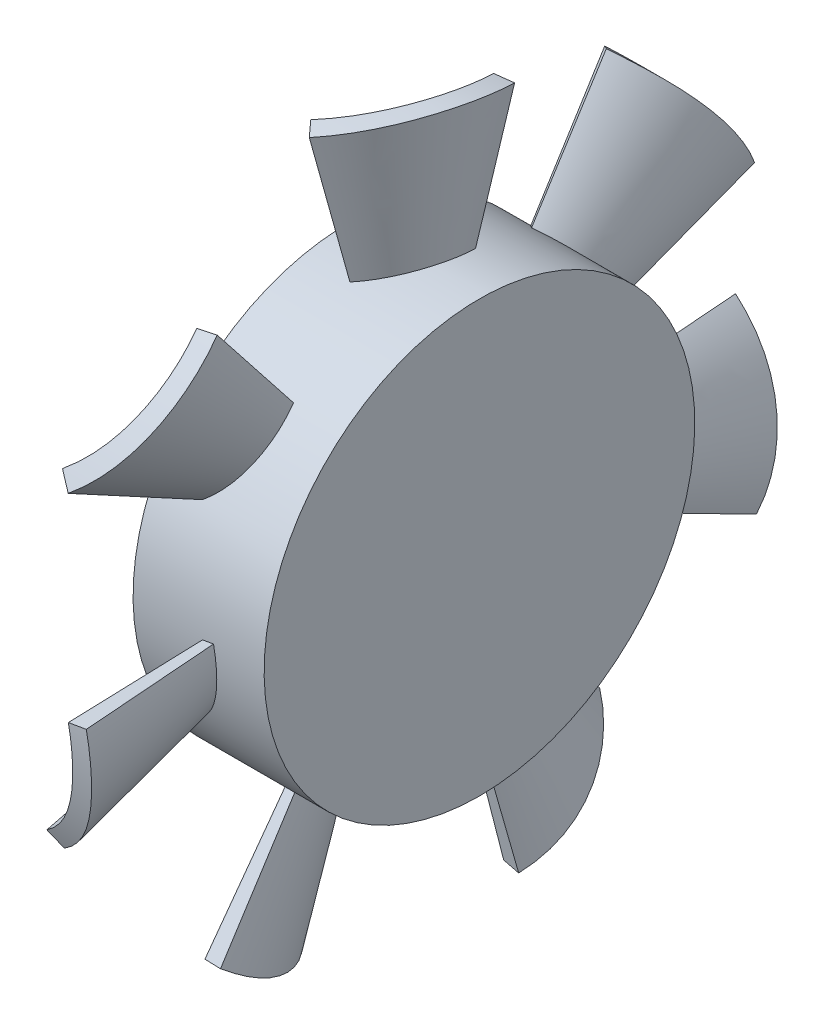
SolidWorks part; units mm, degrees
material "PW100:Mi:0:30:C1:0:1:2:Re:16:"
ref_plane "Front" through (0, 0, 0) normal (0, 0, 1) x (1, 0, 0)
ref_plane "Top" through (0, 0, 0) normal (0, 1, 0) x (1, 0, 0)
ref_plane "Right" through (0, 0, 0) normal (1, 0, 0) x (0, 0, -1)
sketch "Support-Front" plane through (0, 0, 0) normal (0, 0, 1) x (1, 0, 0)
  line L0 (-10, 0) -> (-3, 0) construction
  line L1 (-10, -11.5) -> (-10, 11.5)
  line L2 (-10, 11.5) -> (-3, 11.5)
  line L3 (-10, -11.5) -> (-3, -11.5)
  line L4 (-3, 11.5) -> (-3, -11.5)
  line L5 (-6.5, 11.5) -> (-6.5, -11.5) construction
  line L6 (-3, 11.5) -> (0, 11.5) construction
  line L7 (-3, -11.5) -> (0, -11.5) construction
  line L8 (0, 11.5) -> (0, -11.5) construction
  line L11 (-6.5, 11.5) -> (-6.5, 18.8) construction
  line L12 (-6.5, -11.5) -> (-6.5, -18.8) construction
  point P12 (0, 0)
  point P14 (-6.5, 0)
  dimension "Width" = 10
  dimension "Diam-Body" = 23
  dimension "Diam-Fan" = 37.6
  dimension "Dist-Fan" = 3
sketch "Support-Right" plane through (0, 0, 0) normal (1, 0, 0) x (0, 0, -1)
  circle A0 centre (0, 0) radius 18.8
sketch "Support-Fan-Blade-Top" plane through (0, 0, 0) normal (0, 1, 0) x (-1, 0, 0)
  line L0 (6.5, 0) -> (8.8029, 3.2889) construction
  line L1 (6.1501, -3.9998) -> (8.8029, 3.2889) construction
  line L2 (7.4765, -0.3554) -> (6.5, 0) construction
  line L4 (10, 0) -> (8.8029, 3.2889) construction
  line L5 (10, 0) -> (3, 0) construction
  line L6 (8.1601, 4.055) -> (8.8029, 3.2889)
  line L7 (5.1653, -4.1734) -> (6.1501, -3.9998)
  arc A0 (8.8029, 3.2889) -> (6.1501, -3.9998) centre (13.7887, -2.6529) ccw
  arc A1 (8.1601, 4.055) -> (5.1653, -4.1734) centre (13.7887, -2.6529) ccw
  dimension "D2" = 1
  dimension "D1" = 15
  dimension "D3" = 70
  dimension "Angle-Fan-Blade" = 110
ref_plane "Plane-Angle-Fan-Blade" through (-5.7396, 0, -2.0891) normal (-0.9397, 0, -0.342) x (-0.342, 0, 0.9397)
ref_plane "Plane-Top-Fan-Blade" through (0, 18.8, 0) normal (0, 1, 0) x (-1, 0, 0)
sketch "Sketch-Blade-Bottom" plane through (0, 0, 0) normal (0, 1, 0) x (1, 0, 0)
  point P0 (-6.5, 0)
sketch "Sketch-Blade-Top" plane through (0, 18.8, 0) normal (0, 1, 0) x (-1, 0, 0)
  line L2 (8.8029, 3.2889) -> (8.1601, 4.055)
  line L3 (5.1653, -4.1734) -> (6.1501, -3.9998)
  line L4 (8.8029, 3.2889) -> (8.1601, 4.055)
  line L5 (5.1653, -4.1734) -> (6.1501, -3.9998)
  arc A3 (8.1601, 4.055) -> (5.1653, -4.1734) centre (13.7887, -2.6529) ccw
  arc A4 (8.8029, 3.2889) -> (6.1501, -3.9998) centre (13.7887, -2.6529) ccw
  arc A5 (8.1601, 4.055) -> (5.1653, -4.1734) centre (13.7887, -2.6529) ccw
  arc A6 (8.8029, 3.2889) -> (6.1501, -3.9998) centre (13.7887, -2.6529) ccw
  dimension "D1" = 0
sketch "Sketch5" plane through (0, 0, 0) normal (0, 0, 1) x (1, 0, 0)
  line L0 (-3, 11.5) -> (-3, -11.5) construction
  line L1 (-10, -11.5) -> (-10, 11.5) construction
  line L4 (-3, 11.5) -> (-3, 0)
  line L5 (-10, 0) -> (-10, 11.5)
  line L6 (-10, 0) -> (-3, 0)
  line L7 (-10, 11.5) -> (-3, 11.5) construction
  line L8 (-10, 0) -> (-3, 0) construction
  line L9 (-10, 0) -> (-3, 0) construction
  line L10 (-10, 11.5) -> (-3, 11.5)
revolve "Body" add sketch "Sketch5" angle 360 about L9
loft "Loft-Fan-Blade" add profiles "Sketch-Blade-Top", "Sketch-Blade-Bottom"
pattern_circular "CirPattern1" count 7 over 360 about axis through (-10, 0, 0) along (1, 0, 0) of "Loft-Fan-Blade"
sketch "Sketch-Cut-Blade" plane through (0, 0, 0) normal (1, 0, 0) x (0, 0, -1)
  circle A0 centre (0, 0) radius 18.8 construction
  circle A1 centre (0, 0) radius 18.8
extrude "Cut-Fan-Blade" cut sketch "Sketch-Cut-Blade" against normal through all flip side to cut
equation "\"Angle-Blade@Plane-Angle-Fan-Blade\" = \"Angle-Fan-Blade@Support-Fan-Blade-Top\""
